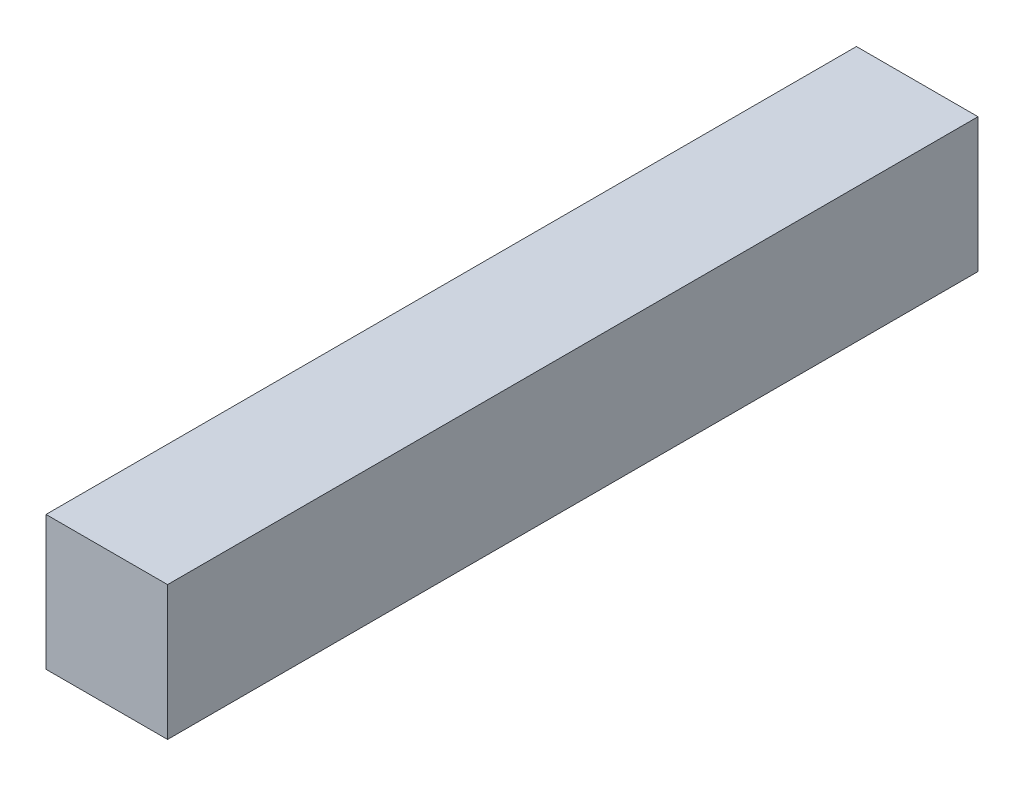
SolidWorks part; units mm, degrees
material "1023 Carbon Steel Sheet (SS)"
ref_plane "Front Plane" through (0, 0, 0) normal (0, 0, 1) x (1, 0, 0)
ref_plane "Top Plane" through (0, 0, 0) normal (0, 1, 0) x (1, 0, 0)
ref_plane "Right Plane" through (0, 0, 0) normal (1, 0, 0) x (0, 0, -1)
sketch "Sketch1" plane through (0, 0, 0) normal (0, 0, 1) x (1, 0, 0)
  line L1 (0, 0) -> (6, 0)
  line L2 (0, 0) -> (0, 6.62)
  line L3 (0, 6.62) -> (6, 6.62)
  line L4 (6, 0) -> (6, 6.62)
  dimension "D1" = 6.62
  dimension "D2" = 6
extrude "Boss-Extrude1" add sketch "Sketch1" along normal blind 40
